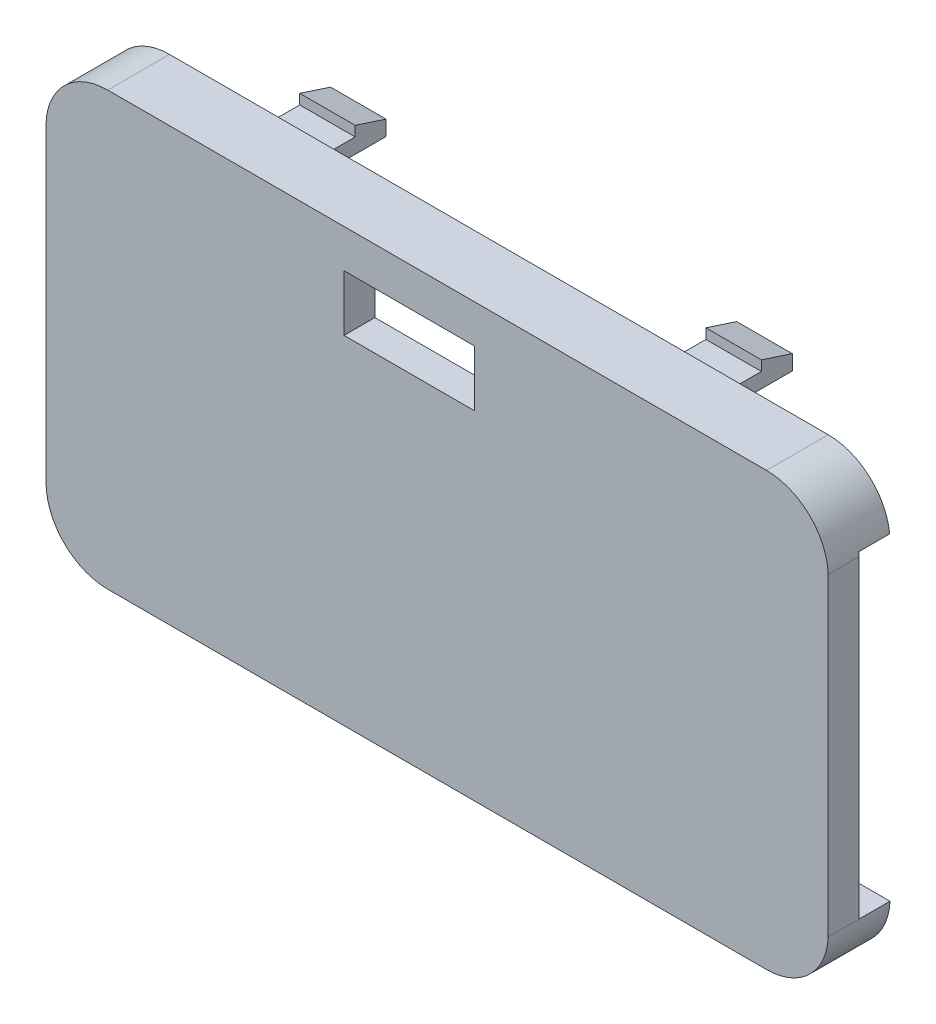
SolidWorks part; units mm, degrees
ref_plane "前视基准面" through (0, 0, 0) normal (0, 0, 1) x (1, 0, 0)
ref_plane "上视基准面" through (0, 0, 0) normal (0, 1, 0) x (1, 0, 0)
ref_plane "右视基准面" through (0, 0, 0) normal (1, 0, 0) x (0, 0, -1)
sketch "草图1" plane through (0, 0, 46.2471) normal (0, 0, 1) x (1, 0, 0)
  line L11 (-18.9357, -5.6321) -> (13.0643, -5.6321) construction
  line L13 (13.0643, 12.3679) -> (-18.9357, 12.3679) construction
  line L15 (-20.4357, 10.8679) -> (-20.4357, -4.1321) construction
  line L16 (13.0643, -7.1321) -> (-18.9357, -7.1321) construction
  line L17 (13.0643, 13.8679) -> (-18.9357, 13.8679) construction
  line L24 (-18.9357, -5.6321) -> (13.0643, -5.6321)
  line L25 (13.0643, 12.3679) -> (-18.9357, 12.3679)
  line L26 (-20.4357, 10.8679) -> (-20.4357, -4.1321)
  line L27 (13.0643, -7.1321) -> (-18.9357, -7.1321)
  line L28 (13.0643, 13.8679) -> (-18.9357, 13.8679)
  line L29 (-21.9357, 10.8679) -> (-21.9357, -4.1321)
  line L30 (14.5643, 10.8679) -> (14.5643, -4.1321)
  line L31 (16.0617, -4.2571) -> (16.0617, 10.9929)
  arc A16 (13.0643, -5.6321) -> (14.5643, -4.1321) centre (13.0643, -4.1321) ccw construction
  arc A17 (14.5643, 10.8679) -> (13.0643, 12.3679) centre (13.0643, 10.8679) ccw construction
  arc A18 (-18.9357, 12.3679) -> (-20.4357, 10.8679) centre (-18.9357, 10.8679) ccw construction
  arc A19 (-20.4357, -4.1321) -> (-18.9357, -5.6321) centre (-18.9357, -4.1321) ccw construction
  arc A20 (-21.9357, -4.1321) -> (-18.9357, -7.1321) centre (-18.9357, -4.1321) ccw construction
  arc A21 (13.0643, -7.1321) -> (16.0617, -4.2571) centre (13.0643, -4.1321) ccw construction
  arc A22 (16.0617, 10.9929) -> (13.0643, 13.8679) centre (13.0643, 10.8679) ccw construction
  arc A23 (-18.9357, 13.8679) -> (-21.9357, 10.8679) centre (-18.9357, 10.8679) ccw construction
  arc A24 (13.0643, -5.6321) -> (14.5643, -4.1321) centre (13.0643, -4.1321) ccw
  arc A25 (14.5643, 10.8679) -> (13.0643, 12.3679) centre (13.0643, 10.8679) ccw
  arc A26 (-18.9357, 12.3679) -> (-20.4357, 10.8679) centre (-18.9357, 10.8679) ccw
  arc A27 (-20.4357, -4.1321) -> (-18.9357, -5.6321) centre (-18.9357, -4.1321) ccw
  arc A28 (-21.9357, -4.1321) -> (-18.9357, -7.1321) centre (-18.9357, -4.1321) ccw
  arc A29 (13.0643, -7.1321) -> (16.0617, -4.2571) centre (13.0643, -4.1321) ccw
  arc A30 (16.0617, 10.9929) -> (13.0643, 13.8679) centre (13.0643, 10.8679) ccw
  arc A31 (-18.9357, 13.8679) -> (-21.9357, 10.8679) centre (-18.9357, 10.8679) ccw
extrude "凸台-拉伸1" add sketch "草图1" along normal blind 1.5
sketch "草图4" plane through (0, 0, 47.7471) normal (0, 0, 1) x (1, 0, 0)
  line L12 (-21.9357, 10.8679) -> (-21.9357, -4.1321)
  line L13 (-18.9357, -7.1321) -> (13.0643, -7.1321)
  line L14 (16.0617, -4.2571) -> (16.0617, 10.9929)
  line L15 (13.0643, 13.8679) -> (-18.9357, 13.8679)
  line L16 (-21.9357, 10.8679) -> (-21.9357, -4.1321)
  line L17 (-18.9357, -7.1321) -> (13.0643, -7.1321)
  line L18 (16.0617, -4.2571) -> (16.0617, 10.9929)
  line L19 (13.0643, 13.8679) -> (-18.9357, 13.8679)
  arc A12 (-21.9357, -4.1321) -> (-18.9357, -7.1321) centre (-18.9357, -4.1321) ccw
  arc A13 (13.0643, -7.1321) -> (16.0617, -4.2571) centre (13.0643, -4.1321) ccw
  arc A14 (16.0617, 10.9929) -> (13.0643, 13.8679) centre (13.0643, 10.8679) ccw
  arc A15 (-18.9357, 13.8679) -> (-21.9357, 10.8679) centre (-18.9357, 10.8679) ccw
  arc A16 (-21.9357, -4.1321) -> (-18.9357, -7.1321) centre (-18.9357, -4.1321) ccw
  arc A17 (13.0643, -7.1321) -> (16.0617, -4.2571) centre (13.0643, -4.1321) ccw
  arc A18 (16.0617, 10.9929) -> (13.0643, 13.8679) centre (13.0643, 10.8679) ccw
  arc A19 (-18.9357, 13.8679) -> (-21.9357, 10.8679) centre (-18.9357, 10.8679) ccw
  dimension "D1" = 0
extrude "凸台-拉伸2" add sketch "草图4" along normal blind 1.5
sketch "草图6" plane through (-21.9357, 0, 0) normal (-1, 0, 0) x (0, 0, 1)
  line L4 (44.9284, 8.6369) -> (44.9284, -1.6131)
  line L5 (44.9284, -1.6131) -> (48.2184, -1.6131)
  line L6 (48.2184, -1.6131) -> (48.2184, 8.6369)
  line L7 (48.2184, 8.6369) -> (44.9284, 8.6369)
  line L8 (44.9284, 8.6369) -> (44.9284, -1.6131)
  line L9 (44.9284, -1.6131) -> (48.7312, -1.6131)
  line L10 (48.7312, -1.6131) -> (48.7312, 8.6369)
  line L11 (48.7312, 8.6369) -> (44.9284, 8.6369)
  dimension "D1" = 0
sketch "草图7" plane through (16.0617, 0, 0) normal (1, 0, 0) x (0, 0, -1)
  line L0 (-46.2471, 11.1894) -> (-47.7537, 11.1894)
  line L1 (-46.2471, 10.9929) -> (-46.2471, 13.8679) construction
  line L2 (-47.7537, 11.1894) -> (-47.7471, -4.2571)
  line L3 (-49.2471, -4.2571) -> (-46.2471, -4.2571) construction
  line L4 (-47.7471, -4.2571) -> (-46.2471, -4.2571)
  line L5 (-46.2471, -4.2571) -> (-46.2471, 11.1894)
extrude "切除-拉伸2" cut sketch "草图7" against normal blind 1.5
sketch "草图8" plane through (0, 0, 49.2471) normal (0, 0, 1) x (1, 0, 0)
  line L1 (-7.4599, 12.0069) -> (-1.1175, 12.0069)
  line L2 (-7.4599, 12.0069) -> (-7.4599, 9.284)
  line L3 (-7.4599, 9.284) -> (-1.1175, 9.284)
  line L4 (-1.1175, 12.0069) -> (-1.1175, 9.284)
extrude "切除-拉伸3" cut sketch "草图8" against normal blind 1.5
sketch "草图9" plane through (0, 0, 46.2471) normal (0, 0, -1) x (-1, 0, 0)
  line L0 (0, 12.3679) -> (0, -5.6321) construction
  line L1 (2.8993, -8.9751) -> (2.8993, 19.0661) construction
  line L3 (-8.3138, 13.4042) -> (-5.6176, 13.4042)
  line L4 (-8.3138, 13.4042) -> (-8.3138, 12.673)
  line L5 (-8.3138, 12.673) -> (-5.6176, 12.673)
  line L6 (-5.6176, 13.4042) -> (-5.6176, 12.673)
  line L18 (14.1125, 12.673) -> (11.4163, 12.673)
  line L19 (11.4163, 13.4042) -> (11.4163, 12.673)
  line L20 (14.1125, 13.4042) -> (11.4163, 13.4042)
  line L21 (14.1125, 13.4042) -> (14.1125, 12.673)
  line L22 (-13.0643, 12.3679) -> (18.9357, 12.3679) construction
  line L23 (18.9357, -5.6321) -> (-13.0643, -5.6321) construction
  line L24 (0, 3.3679) -> (-23.9851, 3.3679) construction
  line L25 (14.1125, -6.6684) -> (14.1125, -5.9371)
  line L26 (14.1125, -6.6684) -> (11.4163, -6.6684)
  line L27 (11.4163, -6.6684) -> (11.4163, -5.9371)
  line L28 (14.1125, -5.9371) -> (11.4163, -5.9371)
  line L29 (-8.3138, -5.9371) -> (-5.6176, -5.9371)
  line L30 (-5.6176, -6.6684) -> (-5.6176, -5.9371)
  line L31 (-8.3138, -6.6684) -> (-5.6176, -6.6684)
  line L32 (-8.3138, -6.6684) -> (-8.3138, -5.9371)
extrude "凸台-拉伸4" add sketch "草图9" along normal blind 3
sketch "草图10" plane through (8.3138, 0, 0) normal (1, 0, 0) x (0, 0, -1)
  line L0 (-43.2471, 13.4042) -> (-46.2471, 13.4042) construction
  line L1 (-44.7471, 13.4042) -> (-44.7471, 13.8925)
  line L2 (-44.7471, 13.8925) -> (-43.2471, 13.4042)
  line L3 (-43.2471, 13.4042) -> (-44.7471, 13.4042)
extrude "凸台-拉伸6" add sketch "草图10" against normal up to surface (22.4264 mm away) up to face at (-14.1125, 13.0386, 44.7471)
sketch "草图11" plane through (-11.4163, 0, 0) normal (1, 0, 0) x (0, 0, -1)
  line L0 (-44.7471, 13.4042) -> (-43.2471, 13.4042)
  line L6 (-46.2471, 13.4042) -> (-46.2471, 12.673)
  line L7 (-46.2471, 12.673) -> (-43.2471, 12.673)
  line L8 (-43.2471, 12.673) -> (-43.2471, 13.4042)
  line L9 (-43.2471, 13.4042) -> (-44.7471, 13.8925)
  line L10 (-44.7471, 13.8925) -> (-44.7471, 13.4042)
  line L11 (-44.7471, 13.4042) -> (-46.2471, 13.4042)
  line L15 (-43.2471, 13.4042) -> (-44.7471, 13.8925)
  line L16 (-44.7471, 13.8925) -> (-44.7471, 13.4042)
  dimension "D1" = 0
extrude "切除-拉伸4" cut sketch "草图11" along normal up to surface (17.0338 mm away) up to face at (5.6176, 13.1117, 44.7471)
ref_plane "基准面1" through (0, 3.3679, 0) normal (0, -1, 0) x (-1, 0, 0)
mirror "镜向1" about plane through (0, 3.3679, 0) normal (0, -1, 0) of "凸台-拉伸6"
mirror "镜向2" about plane through (0, 3.3679, 0) normal (0, -1, 0) of "切除-拉伸4"
extrude "切除-拉伸5" cut sketch "草图6" against normal blind 3.0248
